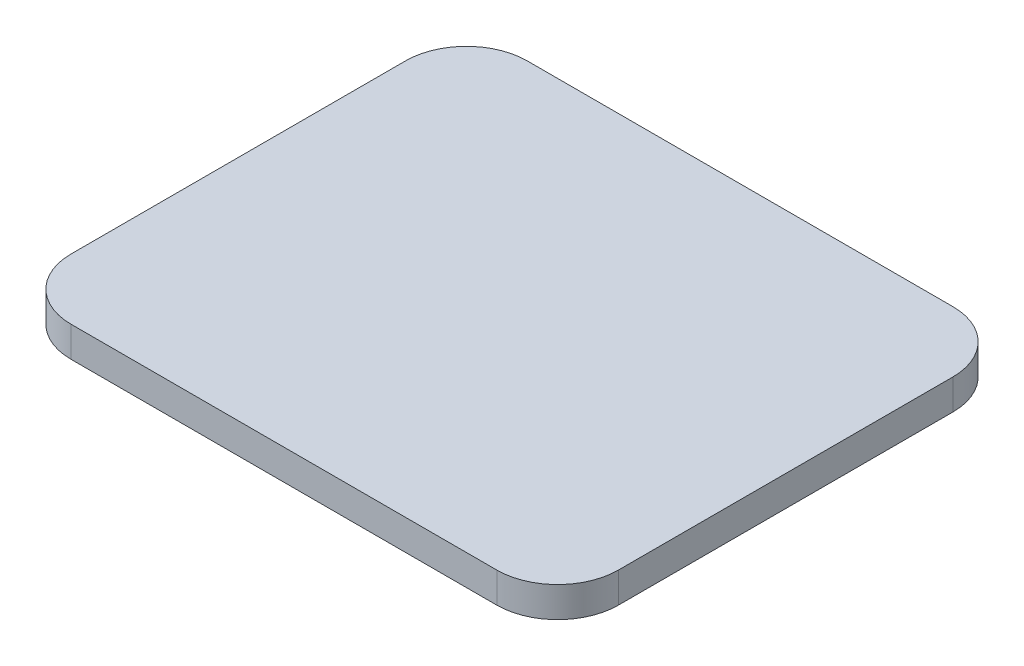
SolidWorks part; units mm, degrees
ref_plane "Front Plane" through (0, 0, 0) normal (0, 0, 1) x (1, 0, 0)
ref_plane "Top Plane" through (0, 0, 0) normal (0, 1, 0) x (1, 0, 0)
ref_plane "Right Plane" through (0, 0, 0) normal (1, 0, 0) x (0, 0, -1)
sketch "Sketch1" plane through (0, 0, 0) normal (0, 1, 0) x (1, 0, 0)
  line L5 (2, 0) -> (16, 0)
  line L6 (0, 2) -> (0, 13)
  line L7 (2, 15) -> (16, 15)
  line L8 (18, 2) -> (18, 13)
  arc A2 (2, 15) -> (0, 13) centre (2, 13) ccw
  arc A3 (0, 2) -> (2, 0) centre (2, 2) ccw
  arc A4 (16, 0) -> (18, 2) centre (16, 2) ccw
  arc A5 (18, 13) -> (16, 15) centre (16, 13) ccw
  point P7 (0, 15)
  point P11 (0, 0)
  point P14 (18, 0)
  point P17 (18, 15)
  dimension "D3" = 2
  dimension "D4" = 2
  dimension "D1" = 18
  dimension "D2" = 15
extrude "Boss-Extrude1" add sketch "Sketch1" along normal blind 1
